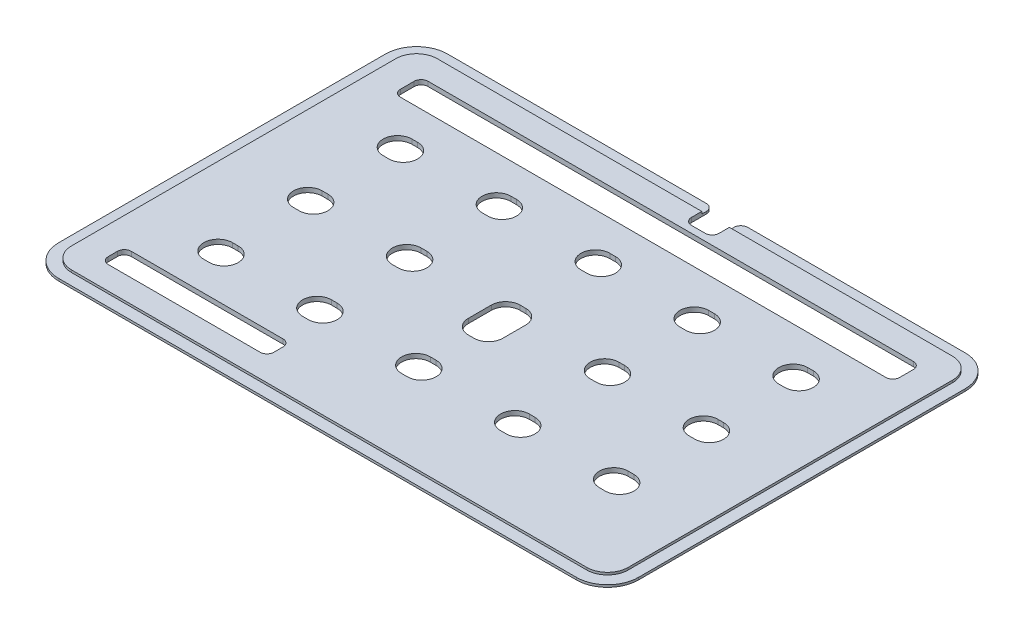
SolidWorks part; units mm, degrees
ref_plane "Front Plane" through (0, 0, 0) normal (0, 0, 1) x (1, 0, 0)
ref_plane "Top Plane" through (0, 0, 0) normal (0, 1, 0) x (1, 0, 0)
ref_plane "Right Plane" through (0, 0, 0) normal (1, 0, 0) x (0, 0, -1)
sketch "Sketch1" plane through (0, 0, 0) normal (0, 1, 0) x (1, 0, 0)
  line L1 (-126, -84.5) -> (126, -84.5)
  line L2 (-126, -84.5) -> (-126, 84.5)
  line L3 (-126, 84.5) -> (126, 84.5)
  line L4 (126, -84.5) -> (126, 84.5)
  line L5 (-126, -84.5) -> (126, 84.5) construction
  line L6 (-126, 84.5) -> (126, -84.5) construction
  point P0 (0, 0)
  dimension "D1" = 252
  dimension "D2" = 169
extrude "Outer Profile" add sketch "Sketch1" along normal blind 1
sketch "Sketch2" plane through (0, 1, 0) normal (0, 1, 0) x (1, 0, 0)
  line L0 (-126, 84.5) -> (-126, -84.5) construction
  line L1 (-121, -79.5) -> (121, -79.5)
  line L2 (-121, -79.5) -> (-121, 79.5)
  line L3 (-121, 79.5) -> (121, 79.5)
  line L4 (121, -79.5) -> (121, 79.5)
  line L5 (-121, -79.5) -> (121, 79.5) construction
  line L6 (-121, 79.5) -> (121, -79.5) construction
  line L7 (126, 84.5) -> (-126, 84.5) construction
  point P0 (0, 0)
  dimension "D1" = 5
  dimension "D2" = 5
extrude "Inner Profile" add sketch "Sketch2" along normal blind 1
fillet "Fillet1" radius 9 4 edges at (121, 1.5, 79.5) (121, 1.5, -79.5) (-121, 1.5, -79.5) (-121, 1.5, 79.5)
fillet "Fillet2" radius 13.5 4 edges at (-126, 0.5, -84.5) (126, 0.5, -84.5) (126, 0.5, 84.5) (-126, 0.5, 84.5)
sketch "Sketch3" plane through (0, 2, 0) normal (0, 1, 0) x (1, 0, 0)
  line L0 (0, 0) -> (0, -50000) construction
  line L1 (-109.5, -68.5) -> (109.5, -68.5) construction
  line L2 (-109.5, -68.5) -> (-109.5, 68.5) construction
  line L3 (-109.5, 68.5) -> (109.5, 68.5) construction
  line L4 (109.5, -68.5) -> (109.5, 68.5) construction
  line L5 (-109.5, -68.5) -> (109.5, 68.5) construction
  line L6 (-109.5, 68.5) -> (109.5, -68.5) construction
  line L7 (-1.25, -40.5) -> (1.25, -40.5) construction
  line L8 (-1.25, -34.25) -> (1.25, -34.25)
  line L9 (-1.25, -46.75) -> (1.25, -46.75)
  arc A0 (-1.25, -34.25) -> (-1.25, -46.75) centre (-1.25, -40.5) ccw
  arc A1 (1.25, -46.75) -> (1.25, -34.25) centre (1.25, -40.5) ccw
  point P0 (0, 0)
  point P5 (0, -40.5)
  point P9 (0, -40.5)
  dimension "D6" = 15
  dimension "D1" = 219
  dimension "D2" = 137
  dimension "D4" = 28
  dimension "D5" = 12.5
chamfer "Chamfer" [suppressed] distance 0.5 angle 45
extrude "Cutout" cut sketch "Sketch3" against normal through all
pattern_linear "Cutouts" count 3 spacing 43 along (-1, 0, 0) count 3 spacing 39 along (0, 0, -1) of "Cutout"
mirror "Mirror1" about plane through (0, 0, 0) normal (1, 0, 0) of "Cutouts"
sketch "Sketch4" plane through (0, 2, 0) normal (0, 1, 0) x (1, 0, 0)
  line L0 (0, 79.5) -> (0, 0) construction
  line L1 (-108.5, 57) -> (108.5, 57)
  line L2 (-108.5, 57) -> (-108.5, 69)
  line L3 (-108.5, 69) -> (108.5, 69)
  line L4 (108.5, 57) -> (108.5, 69)
  line L5 (112, 79.5) -> (-112, 79.5) construction
  line L7 (-109.5, 68.5) -> (109.5, 68.5) construction
  dimension "D1" = 0.5
  dimension "D2" = 12
  dimension "D3" = 217
extrude "Message Window" cut sketch "Sketch4" against normal through all
fillet "Message Window Corners" radius 3 4 edges at (108.5, 1, -57) (-108.5, 1, -57) (108.5, 1, -69) (-108.5, 1, -69)
chamfer "Edge Chamfer" [suppressed] distance 1 angle 45
sketch "Sketch5" plane through (0, 2, 0) normal (0, 1, 0) x (1, 0, 0)
  line L0 (3, 72) -> (3, 84.5)
  line L1 (3, 84.5) -> (15, 84.5)
  line L2 (15, 84.5) -> (15, 72)
  line L5 (112.5, 84.5) -> (-112.5, 84.5) construction
  line L6 (3, 72) -> (15, 72)
  line L7 (9, 72) -> (9, 93.2237) construction
  line L8 (-121, 70.5) -> (-121, -70.5) construction
  line L9 (105.5, 69) -> (-105.5, 69) construction
  dimension "D1" = 12
  dimension "D2" = 130
  dimension "D3" = 3
extrude "Camera Cutout" cut sketch "Sketch5" against normal through all
fillet "Fillet3" radius 3 4 edges at (15, 0.5, -84.5) (15, 1, -72) (3, 1, -72) (3, 0.5, -84.5)
sketch "Sketch6" plane through (0, 2, 0) normal (0, 1, 0) x (1, 0, 0)
  line L0 (-7.5, -1.5) -> (-7.5, -11.5)
  line L1 (-1.25, -17.75) -> (1.25, -17.75)
  line L2 (7.5, -11.5) -> (7.5, -1.5)
  line L3 (-1.25, -7.75) -> (1.25, -7.75) construction
  arc A0 (-1.25, 4.75) -> (-1.25, -7.75) centre (-1.25, -1.5) ccw construction
  arc A1 (-7.5, -11.5) -> (-1.25, -17.75) centre (-1.25, -11.5) ccw
  arc A2 (1.25, -17.75) -> (7.5, -11.5) centre (1.25, -11.5) ccw
  arc A3 (1.25, -7.75) -> (1.25, 4.75) centre (1.25, -1.5) ccw construction
  dimension "D1" = 10
extrude "Cut-Extrude1" cut sketch "Sketch6" against normal through all and the other way through all
sketch "Sketch7" plane through (0, 2, 0) normal (0, 1, 0) x (1, 0, 0)
  line L0 (-126, 71) -> (-126, -71) construction
  line L1 (-109, -69.5) -> (-37, -69.5)
  line L2 (-109, -69.5) -> (-109, -59.5)
  line L3 (-109, -59.5) -> (-37, -59.5)
  line L4 (-37, -69.5) -> (-37, -59.5)
  line L5 (-112.5, -84.5) -> (112.5, -84.5) construction
  dimension "D1" = 17
  dimension "D2" = 10
  dimension "D3" = 15
  dimension "D4" = 72
extrude "Cut-Extrude2" cut sketch "Sketch7" against normal blind 10
fillet "Fillet5" radius 3 4 edges at (-109, 1, 69.5) (-37, 1, 69.5) (-37, 1, 59.5) (-109, 1, 59.5)
